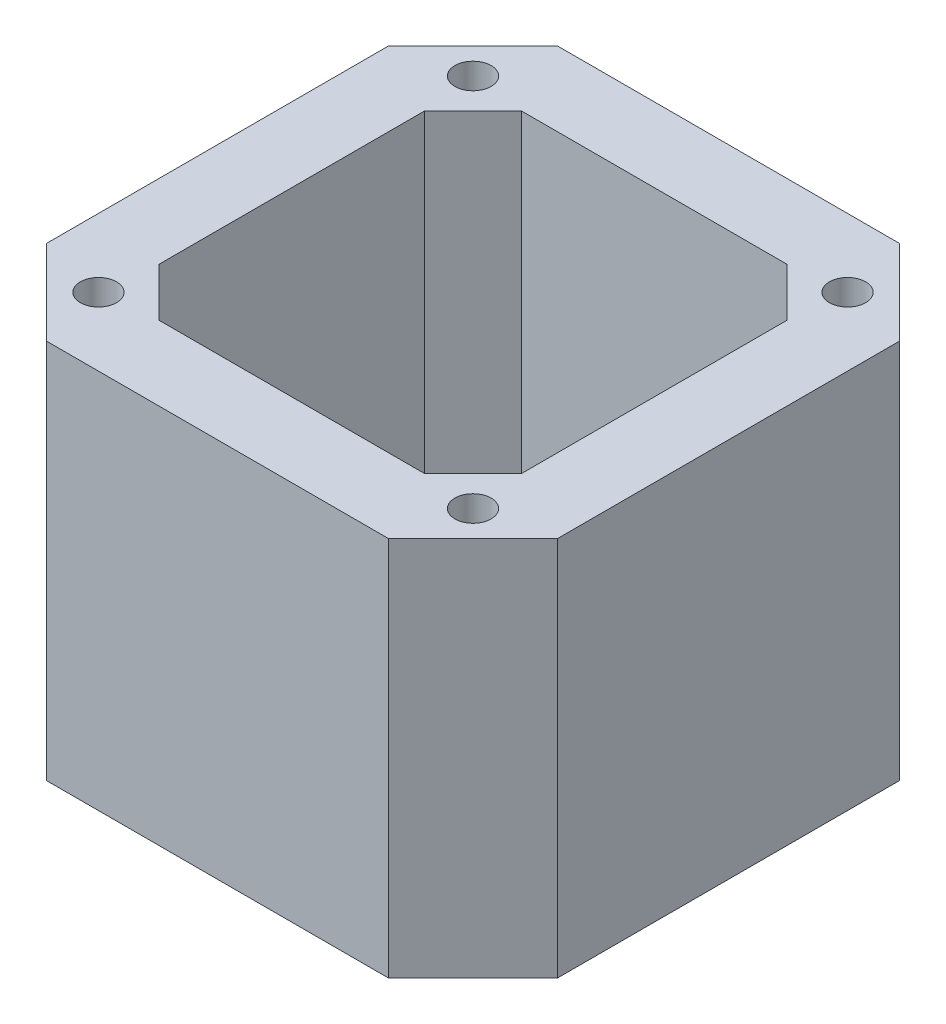
SolidWorks part; units mm, degrees
ref_plane "Front Plane" through (0, 0, 0) normal (0, 0, 1) x (1, 0, 0)
ref_plane "Top Plane" through (0, 0, 0) normal (0, 1, 0) x (1, 0, 0)
ref_plane "Right Plane" through (0, 0, 0) normal (1, 0, 0) x (0, 0, -1)
sketch "Sketch1" plane through (0, 0, 0) normal (0, 1, 0) x (1, 0, 0)
  line L0 (-21.15, 14.15) -> (-14.15, 21.15)
  line L1 (-14.15, 21.15) -> (14.15, 21.15)
  line L2 (-21.15, 14.15) -> (-21.15, -14.15)
  line L3 (-14.15, -21.15) -> (14.15, -21.15)
  line L4 (21.15, 14.15) -> (21.15, -14.15)
  line L5 (-21.15, 21.15) -> (21.15, -21.15) construction
  line L6 (-21.15, -21.15) -> (21.15, 21.15) construction
  line L7 (14.15, 21.15) -> (21.15, 14.15)
  line L8 (14.15, -21.15) -> (21.15, -14.15)
  line L9 (-21.15, -14.15) -> (-14.15, -21.15)
  point P0 (0, 0)
  dimension "D1" = 42.3
extrude "Boss-Extrude1" add sketch "Sketch1" along normal blind 31.5
sketch "Sketch2" plane through (0, 31.5, 0) normal (0, 1, 0) x (1, 0, 0)
  line L1 (-15.5, 15.5) -> (15.5, 15.5) construction
  line L2 (-15.5, 15.5) -> (-15.5, -15.5) construction
  line L3 (-15.5, -15.5) -> (15.5, -15.5) construction
  line L4 (15.5, 15.5) -> (15.5, -15.5) construction
  line L5 (-15.5, 15.5) -> (15.5, -15.5) construction
  line L6 (-15.5, -15.5) -> (15.5, 15.5) construction
  circle A0 centre (-15.5, 15.5) radius 1.5
  circle A1 centre (15.5, 15.5) radius 1.5
  circle A2 centre (-15.5, -15.5) radius 1.5
  circle A3 centre (15.5, -15.5) radius 1.5
  point P0 (0, 0)
  dimension "D2" = 3
  dimension "D1" = 31
extrude "Cut-Extrude1" cut sketch "Sketch2" against normal blind 5
sketch "Sketch3" plane through (0, 31.5, 0) normal (0, 1, 0) x (1, 0, 0)
  line L0 (-15, 11) -> (-11, 15)
  line L1 (-11, 15) -> (11, 15)
  line L2 (-15, 11) -> (-15, -11)
  line L3 (-11, -15) -> (11, -15)
  line L4 (15, 11) -> (15, -11)
  line L5 (-15, 15) -> (15, -15) construction
  line L6 (-15, -15) -> (15, 15) construction
  line L7 (11, 15) -> (15, 11)
  line L8 (11, -15) -> (15, -11)
  line L9 (-15, -11) -> (-11, -15)
  point P0 (0, 0)
  dimension "D1" = 30
  dimension "D2" = 30
extrude "Cut-Extrude3" cut sketch "Sketch3" against normal blind 45
